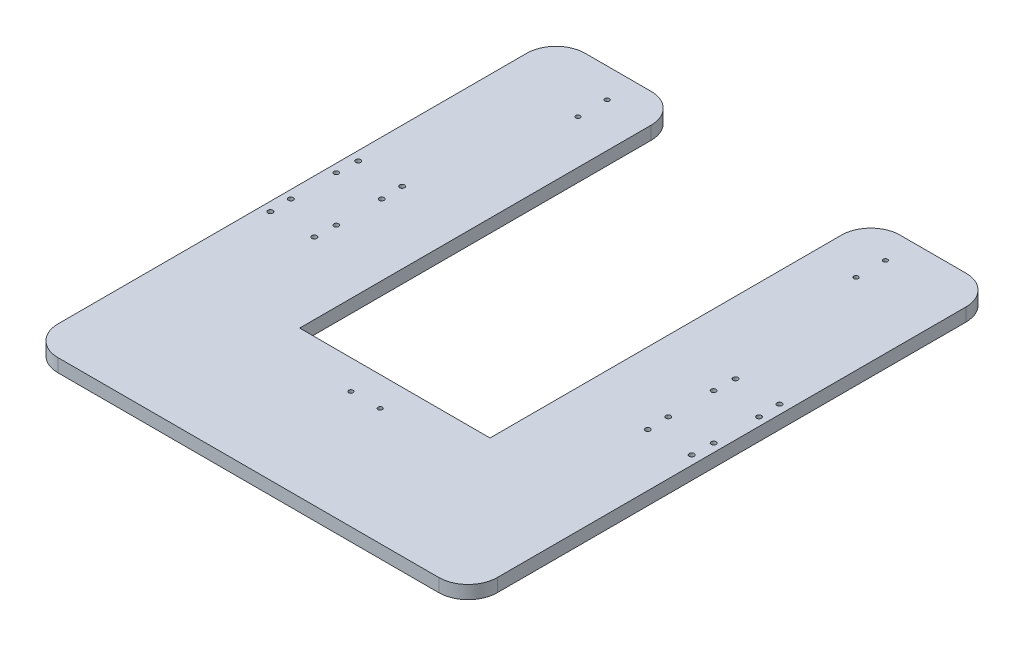
SolidWorks part; units mm, degrees
ref_plane "前视基准面" through (0, 0, 0) normal (0, 0, 1) x (1, 0, 0)
ref_plane "上视基准面" through (0, 0, 0) normal (0, 1, 0) x (1, 0, 0)
ref_plane "右视基准面" through (0, 0, 0) normal (1, 0, 0) x (0, 0, -1)
sketch "草图1" plane through (0, 0, 0) normal (0, 1, 0) x (1, 0, 0)
  line L1 (-150, 180) -> (150, 180)
  line L2 (-150, 180) -> (-150, -180)
  line L3 (-150, -180) -> (150, -180)
  line L4 (150, 180) -> (150, -180)
  line L5 (0, -180) -> (0, 180) construction
  line L6 (-150, 0) -> (150, 0) construction
  point P0 (0, 0)
  dimension "D1" = 360
  dimension "D2" = 300
extrude "凸台-拉伸1" add sketch "草图1" along normal blind 9
sketch "草图2" plane through (0, 9, 0) normal (0, 1, 0) x (1, 0, 0)
  line L0 (0, 180) -> (0, 0) construction
  line L1 (150, 180) -> (-150, 180) construction
  line L3 (-65, 180) -> (65, 180)
  line L4 (-65, 180) -> (-65, -80)
  line L5 (-65, -80) -> (65, -80)
  line L6 (65, 180) -> (65, -80)
  line L7 (0, -80) -> (0, 180) construction
  line L8 (-65, 50) -> (65, 50) construction
  point P5 (0, 50)
  dimension "D1" = 260
  dimension "D2" = 130
extrude "切除-拉伸1" cut sketch "草图2" against normal blind 9
sketch "草图3" plane through (0, 9, 0) normal (0, 1, 0) x (1, 0, 0)
  line L0 (0, 165.1057) -> (0, 0) construction
  line L1 (-65, 180) -> (-65, -80) construction
  line L2 (-65, 180) -> (-150, 180) construction
  line L3 (-65, -80) -> (65, -80) construction
  circle A0 centre (-95, 160) radius 1.5
  circle A1 centre (-95, 140) radius 1.5
  circle A2 centre (95, 140) radius 1.5
  circle A3 centre (95, 160) radius 1.5
  circle A4 centre (-10, -100) radius 1.5
  circle A5 centre (10, -100) radius 1.5
  dimension "D1" = 3
  dimension "D5" = 3
  dimension "D6" = 3
  dimension "D7" = 20
  dimension "D8" = 20
  dimension "D2" = 20
  dimension "D3" = 30
  dimension "D4" = 20
extrude "切除-拉伸2" cut sketch "草图3" against normal blind 10
fillet "圆角1" radius 20 6 edges at (-65, 4.5, -180) (65, 4.5, -180) (150, 4.5, -180) (150, 4.5, 180) (-150, 4.5, 180) (-150, 4.5, -180)
sketch "草图5" plane through (0, 9, 0) normal (0, 1, 0) x (1, 0, 0)
  circle A0 centre (-113.35, 24.35) radius 1.65 construction
  circle A1 centre (-144.35, 24.35) radius 1.65 construction
  circle A2 centre (-143.85, 38.85) radius 1.7 construction
  circle A3 centre (-113.85, 38.85) radius 1.7 construction
  circle A4 centre (-144.35, -6.65) radius 1.65 construction
  circle A5 centre (-143.85, -21.15) radius 1.7 construction
  circle A6 centre (-113.85, -21.15) radius 1.7 construction
  circle A7 centre (-113.35, -6.65) radius 1.65 construction
  circle A8 centre (-113.35, 24.35) radius 1.65
  circle A9 centre (-144.35, 24.35) radius 1.65
  circle A10 centre (-143.85, 38.85) radius 1.7
  circle A11 centre (-113.85, 38.85) radius 1.7
  circle A12 centre (-144.35, -6.65) radius 1.65
  circle A13 centre (-143.85, -21.15) radius 1.7
  circle A14 centre (-113.85, -21.15) radius 1.7
  circle A15 centre (-113.35, -6.65) radius 1.65
extrude "切除-拉伸4" cut sketch "草图5" against normal blind 10
mirror "镜向2" about plane through (0, 0, 0) normal (1, 0, 0) of "切除-拉伸4"
